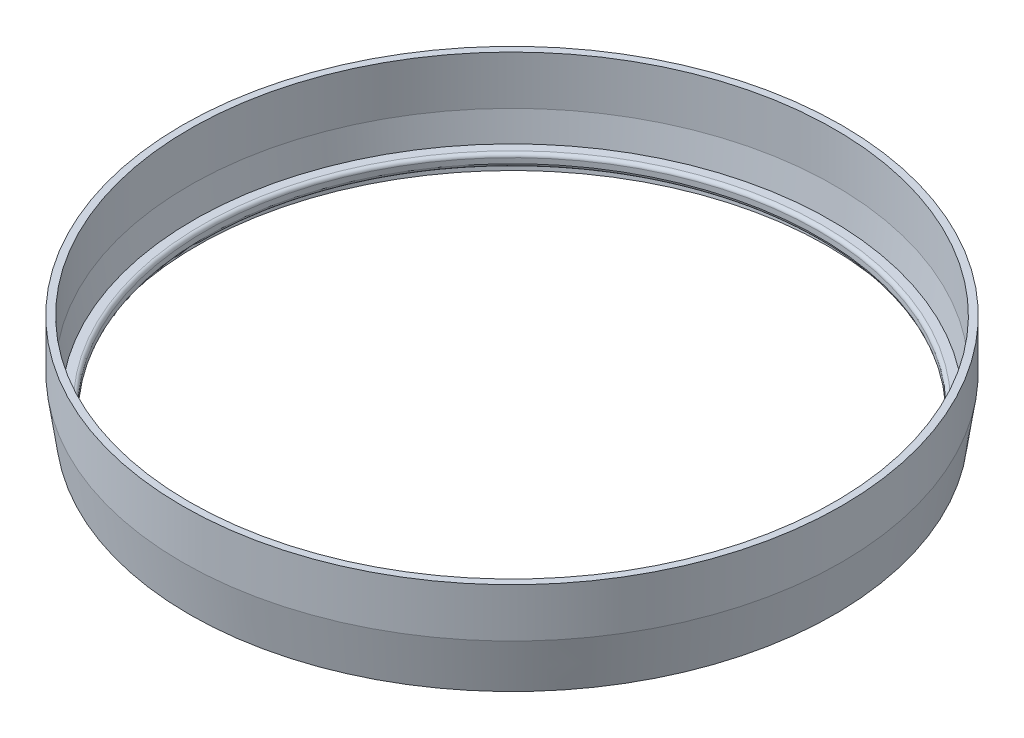
SolidWorks part; units mm, degrees
ref_plane "Front Plane" through (0, 0, 0) normal (0, 0, 1) x (1, 0, 0)
ref_plane "Top Plane" through (0, 0, 0) normal (0, 1, 0) x (1, 0, 0)
ref_plane "Right Plane" through (0, 0, 0) normal (1, 0, 0) x (0, 0, -1)
ref_axis "Axis1" through (0, 55, 0) along (0, -1, 0)
sketch "Sketch1" plane through (0, 0, 0) normal (0, 0, 1) x (1, 0, 0)
  line L11 (0, 55) -> (0, -55) construction
  line L12 (0, 0) -> (45.2788, 0) construction
  line L13 (45.2788, 0) -> (45.4612, 1.25)
  line L14 (45.4612, 1.25) -> (44, 1.25)
  line L15 (44, 1.25) -> (44, 3)
  line L16 (44, 3) -> (45.7165, 3)
  line L18 (46.3, 7) -> (46.3, 14)
  line L19 (46.3, 14) -> (47.3, 14)
  line L20 (47.3, 14) -> (47.3, 7)
  line L23 (46.2788, 0) -> (45.2788, 0)
  line L24 (45.7165, 3) -> (46.3, 7)
  line L25 (47.3, 7) -> (46.2788, 0)
  point P11 (46.2788, 7)
  point P14 (0, 0)
  dimension "D1" = 1
  dimension "D2" = 14
  dimension "D3" = 1.75
  dimension "D4" = 44
  dimension "D5" = 46.3
  dimension "D6" = 1
  dimension "D7" = 98.3
  dimension "D8" = 98.3
  dimension "D9" = 11
  dimension "D10" = 7
revolve "Revolve1" add sketch "Sketch1" angle 360 about axis through (0, 55, 0) along (0, -1, 0)
fillet "Fillet1" radius 0.5 2 edges at (0, 1.25, 44) (0, 3, 44)
